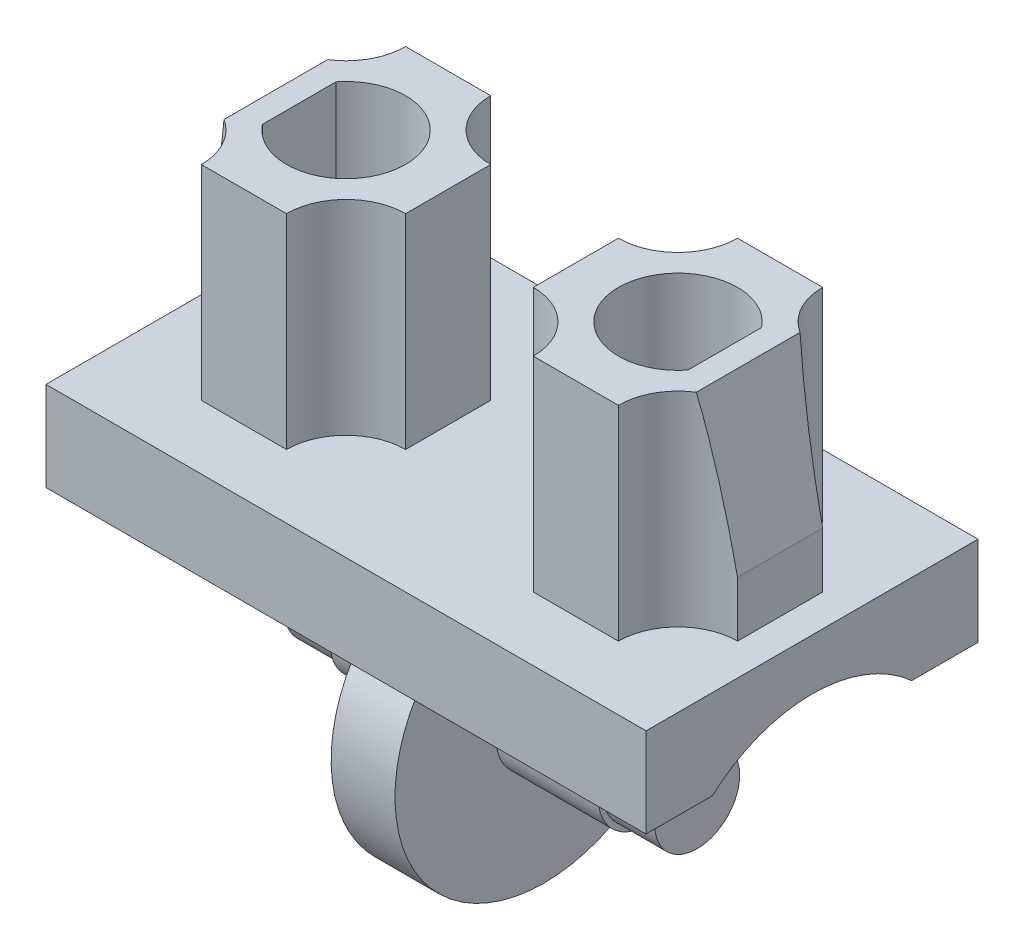
SolidWorks part; units mm, degrees
ref_plane "Front Plane" through (0, 0, 0) normal (0, 0, 1) x (1, 0, 0)
ref_plane "Top Plane" through (0, 0, 0) normal (0, 1, 0) x (1, 0, 0)
ref_plane "Right Plane" through (0, 0, 0) normal (1, 0, 0) x (0, 0, -1)
sketch "Sketch1" plane through (0, 0, 0) normal (0, 1, 0) x (1, 0, 0)
  line L1 (-7.05, -3.9) -> (7.05, -3.9)
  line L2 (-7.05, -3.9) -> (-7.05, 3.9)
  line L3 (-7.05, 3.9) -> (7.05, 3.9)
  line L4 (7.05, -3.9) -> (7.05, 3.9)
  line L5 (-7.05, -3.9) -> (7.05, 3.9) construction
  line L6 (-7.05, 3.9) -> (7.05, -3.9) construction
  point P0 (0, 0)
  dimension "D1" = 14.1
  dimension "D2" = 7.8
extrude "Boss-Extrude1" add sketch "Sketch1" along normal mid plane 2.1
sketch "Sketch2" plane through (0, 0, 0) normal (0, 0, 1) x (1, 0, 0)
  line L0 (-6.3, 1.05) -> (-6.3, 2.35)
  line L1 (-7.05, 1.05) -> (7.05, 1.05) construction
  line L2 (-6.3, 2.35) -> (-5.55, 5.85)
  line L3 (-5.55, 5.85) -> (-1.5, 5.85)
  line L4 (-1.5, 5.85) -> (-1.5, 1.05)
  line L5 (-6.3, 1.05) -> (-1.5, 1.05)
  dimension "D1" = 4.8
  dimension "D2" = 4.8
  dimension "D3" = 0.75
  dimension "D4" = 3.5
  dimension "D5" = 1.5
extrude "Boss-Extrude2" add sketch "Sketch2" along normal mid plane 4.8
sketch "Sketch3" plane through (0, 5.85, 0) normal (0, 1, 0) x (1, 0, 0)
  line L0 (-7.1878, 0) -> (-1.5, 2.4) construction
  line L1 (-1.5, -2.4) -> (-5.55, -2.4) construction
  line L2 (-1.5, -2.4) -> (-1.5, 2.4) construction
  circle A0 centre (-1.5, 2.4) radius 1.4
  circle A1 centre (-1.5, -2.4) radius 1.4
  circle A4 centre (-4.9385, -5.7491) radius 1.4 [skipped]
  circle A5 centre (-9.7369, -5.6226) radius 1.4 [skipped]
  circle A6 centre (-6.3, 2.4) radius 1.4
  circle A7 centre (-6.3, -2.4) radius 1.4
  point P3 (0, 0)
  point P9 (-6.365, 2.4)
  point P21 (0, 0)
  dimension "D1" = 2.8
  dimension "D3" = 6.1734
  dimension "D5" = 4.8
  dimension "D4" = 2
  dimension "D2" = 4
extrude "Cut-Extrude1" cut sketch "Sketch3" against normal up to surface (4.8 mm away) up to face at (0, 1.05, 0)
sketch "Sketch4" plane through (0, 5.85, 0) normal (0, 1, 0) x (1, 0, 0)
  line L1 (-5, 0.866) -> (-5, -0.866)
  line L2 (-6.3, -1) -> (-6.3, 1) construction
  line L3 (7.6068, 0) -> (-7.05, 0) construction
  line L4 (-7.05, 3.9) -> (-7.05, -3.9) construction
  line L5 (-3.9, 2.4) -> (-3.9, -2.4) construction
  line L6 (-2.9, 2.4) -> (-4.9, 2.4) construction
  line L7 (-2.9, -2.4) -> (-4.9, -2.4) construction
  arc A0 (-5, -0.866) -> (-5, 0.866) centre (-3.9, 0) ccw
  point P6 (0, 0)
  dimension "D1" = 2.8
  dimension "D2" = 1.3
extrude "Cut-Extrude2" cut sketch "Sketch4" against normal up to surface (4.8 mm away) up to face at (0, 1.05, 0)
mirror "Mirror1" about plane through (0, 0, 0) normal (1, 0, 0) of "Boss-Extrude2", "Cut-Extrude1", "Cut-Extrude2"
sketch "Sketch5" plane through (0, 0, 0) normal (1, 0, 0) x (0, 0, -1)
  line L0 (0, -6.1722) -> (0, 9.1599) construction
  line L2 (-3.9, 1.05) -> (3.9, 1.05) construction
  circle A0 centre (0, -3.65) radius 3.5
  dimension "D2" = 7
  dimension "D1" = 4.7
extrude "Boss-Extrude3" add sketch "Sketch5" along normal mid plane 1.5
sketch "Sketch6" plane through (0.75, 0, 0) normal (1, 0, 0) x (0, 0, -1)
  circle A0 centre (0, -3.65) radius 1.125
  dimension "D1" = 2.25
extrude "Boss-Extrude4" add sketch "Sketch6" along normal blind 2.4
mirror "Mirror2" about plane through (0, 0, 0) normal (1, 0, 0) of "Boss-Extrude4"
sketch "Sketch7" plane through (3.15, 0, 0) normal (1, 0, 0) x (0, 0, -1)
  circle A0 centre (0, -3.65) radius 1
  dimension "D1" = 2
extrude "Boss-Extrude5" add sketch "Sketch7" along normal blind 1.2
mirror "Mirror3" about plane through (0, 0, 0) normal (1, 0, 0) of "Boss-Extrude5"
sketch "Sketch8" plane through (-7.05, 0, 0) normal (-1, 0, 0) x (0, 0, 1)
  line L0 (-3.9, -1.05) -> (3.9, -1.05) construction
  line L1 (-2.3431, -1.05) -> (2.3431, -1.05)
  arc A0 (2.3431, -1.05) -> (-2.3431, -1.05) centre (0, -3.65) ccw
  arc A1 (-2.3431, -1.05) -> (2.3431, -1.05) centre (0, -3.65) ccw construction
extrude "Cut-Extrude3" cut sketch "Sketch8" against normal up to surface (6.3 mm away) up to face at (-0.75, -3.65, -1.125)
sketch "Sketch9" plane through (7.05, 0, 0) normal (1, 0, 0) x (0, 0, -1)
  line L0 (-3.9, -1.05) -> (3.9, -1.05) construction
  line L1 (-2.3431, -1.05) -> (2.3431, -1.05)
  arc A0 (2.3431, -1.05) -> (-2.3431, -1.05) centre (0, -3.65) ccw
  arc A1 (-2.3431, -1.05) -> (2.3431, -1.05) centre (0, -3.65) ccw construction
extrude "Cut-Extrude4" cut sketch "Sketch9" against normal up to surface (6.3 mm away) up to face at (0.75, -3.65, -1.125)
